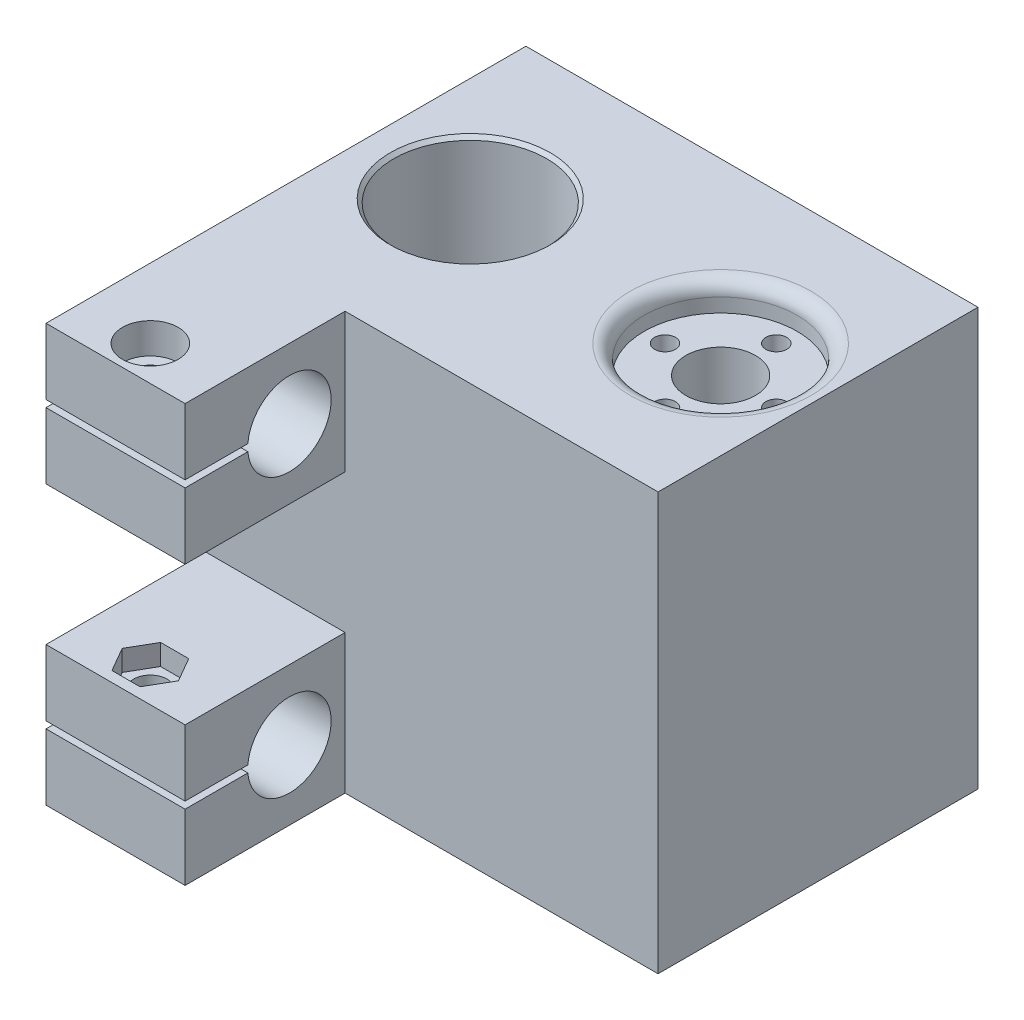
SolidWorks part; units mm, degrees
material "ABS"
ref_plane "Спереди" through (0, 0, 0) normal (0, 0, 1) x (1, 0, 0)
ref_plane "Сверху" through (0, 0, 0) normal (0, 1, 0) x (1, 0, 0)
ref_plane "Справа" through (0, 0, 0) normal (1, 0, 0) x (0, 0, -1)
sketch "Эскиз1" plane through (0, 0, 0) normal (0, 1, 0) x (1, 0, 0)
  line L0 (0, 0) -> (0, 46)
  line L1 (0, 46) -> (65, 46)
  line L2 (65, 46) -> (65, 0)
  line L3 (65, 0) -> (0, 0)
  line L4 (0, 23) -> (65, 23) construction
  line L5 (51, 46) -> (51, 0) construction
  line L6 (15, 46) -> (15, 0) construction
  line L7 (65, 3) -> (0, 3) construction
  circle A0 centre (51, 23) radius 5
  circle A1 centre (15, 23) radius 11
  dimension "D3" = 10
  dimension "D5" = 22
  dimension "D1" = 23
  dimension "D2" = 15
  dimension "D4" = 36
  dimension "D6" = 23
  dimension "D8" = 46
  dimension "D9" = 20
  dimension "D10" = 3
extrude "Бобышка-Вытянуть1" add sketch "Эскиз1" along normal blind 60
sketch "Эскиз3" plane through (0, 0, 0) normal (-1, 0, 0) x (0, 0, 1)
  line L0 (0, 60) -> (23, 60)
  line L1 (0, 60) -> (0, 0) construction
  line L2 (23, 0) -> (0, 0)
  line L3 (0, 40) -> (0, 60)
  line L4 (8, 50) -> (8, 10) construction
  line L5 (0, 20) -> (0, 0)
  line L6 (23, 60) -> (23, 50.5)
  line L7 (23, 40) -> (0, 40)
  line L8 (23, 50.5) -> (13.9791, 50.5)
  line L9 (0, 20) -> (23, 20)
  line L10 (23, 20) -> (23, 10.5)
  line L11 (23, 49.5) -> (13.9791, 49.5)
  line L12 (8, 50) -> (26.9195, 50) construction
  line L13 (23, 49.5) -> (23, 40)
  line L14 (23, 10.5) -> (13.9791, 10.5)
  line L15 (13.9791, 9.5) -> (23, 9.5)
  line L16 (23, 9.5) -> (23, 0)
  line L17 (8, 10) -> (27.7676, 10) construction
  arc A0 (13.9791, 50.5) -> (13.9791, 49.5) centre (8, 50) ccw
  arc A1 (13.9791, 10.5) -> (13.9791, 9.5) centre (8, 10) ccw
  dimension "D1" = 1
  dimension "D2" = 10
  dimension "D4" = 6
  dimension "D8" = 6
  dimension "D3" = 10
  dimension "D5" = 20
  dimension "D6" = 20
  dimension "D7" = 1
  dimension "D9" = 8
  dimension "D10" = 23
extrude "Бобышка-Вытянуть3" add sketch "Эскиз3" against normal blind 20
sketch "Эскиз18" plane through (0, 60, 0) normal (0, 1, 0) x (1, 0, 0)
  circle A0 centre (51, 23) radius 11
  dimension "D1" = 22
extrude "Вырез-Вытянуть8" cut sketch "Эскиз18" against normal blind 4
sketch "Эскиз20" plane through (0, 56, 0) normal (0, 1, 0) x (1, 0, 0)
  line L0 (51, 15) -> (51, 31) construction
  line L1 (43, 23) -> (59, 23) construction
  circle A0 centre (43, 23) radius 1.5
  circle A1 centre (59, 23) radius 1.5
  circle A2 centre (51, 31) radius 1.5
  circle A3 centre (51, 15) radius 1.5
  dimension "D1" = 3
  dimension "D2" = 16
  dimension "D3" = 16
extrude "Вырез-Вытянуть9" cut sketch "Эскиз20" against normal up to surface (56 mm away) up to face at (51, 0, -18)
fillet "Скругление4" radius 2 1 edges at (51, 60, -12)
sketch "Эскиз28" plane through (0, 0, 0) normal (0, -1, 0) x (-1, 0, 0)
  circle A0 centre (-51, 23) radius 11
  dimension "D1" = 22
extrude "Вырез-Вытянуть10" cut sketch "Эскиз28" against normal blind 4
chamfer "Фаска1" distance 0.5 1 edges at (15, 60, -12)
fillet "Скругление5" radius 2 1 edges at (51, 0, -34)
chamfer "Фаска2" distance 0.5 1 edges at (15, 0, -12)
hole_wizard "Цековка для  винта с внутренним шестигранником M41" positions "Эскиз21" profile "Эскиз23" counterbore size "M4" standard "DIN"
sketch "Эскиз21" plane through (0, 60, 0) normal (0, 1, 0) x (1, 0, 0)
  line L0 (10, -23) -> (10, -3.6448) construction
  line L1 (20, -23) -> (0, -23) construction
  line L3 (0, 46) -> (0, -23) construction
  point P0 (10, -18)
  dimension "D1" = 10
  dimension "D2" = 5
sketch "Эскиз23" plane through (10, 60, 18) normal (1, 0, 0) x (0, 0, 1)
  line L0 (0, 0) -> (0, 21.4411)
  line L1 (0, 21.4411) -> (2.4, 19.999)
  line L2 (2.4, 19.999) -> (2.4, 4.4)
  line L3 (2.4, 4.4) -> (4, 4.4)
  line L4 (4, 4.4) -> (4, 0)
  line L5 (4, 0) -> (0, 0)
  line L10 (0, 21.4411) -> (-2.4, 19.999) construction
  line L11 (0, -6.35) -> (0, 107.95) construction
  dimension "Диаметр отверстия" = 4.8
  dimension "Глубина отверстия" = 19.999
  dimension "Диаметр цековки" = 8
  dimension "Глубина цековки" = 4.4
  dimension "Угол заточки сверла" = 118
hole_wizard "Цековка для  винта с внутренним шестигранником M42" positions "Эскиз26" profile "Эскиз27" counterbore size "M4" standard "DIN"
sketch "Эскиз26" plane through (0, 0, 0) normal (0, -1, 0) x (-1, 0, 0)
  line L0 (0, 46) -> (0, -23) construction
  line L1 (-20, -23) -> (0, -23) construction
  point P0 (-10, -18)
  dimension "D1" = 10
  dimension "D2" = 5
sketch "Эскиз27" plane through (10, 0, 18) normal (1, 0, 0) x (0, 0, -1)
  line L0 (0, 0) -> (0, 21.4411)
  line L1 (0, 21.4411) -> (2.4, 19.999)
  line L2 (2.4, 19.999) -> (2.4, 4.4)
  line L3 (2.4, 4.4) -> (4, 4.4)
  line L4 (4, 4.4) -> (4, 0)
  line L5 (4, 0) -> (0, 0)
  line L10 (0, 21.4411) -> (-2.4, 19.999) construction
  line L11 (0, -6.35) -> (0, 107.95) construction
  dimension "Диаметр отверстия" = 4.8
  dimension "Глубина отверстия" = 19.999
  dimension "Диаметр цековки" = 8
  dimension "Глубина цековки" = 4.4
  dimension "Угол заточки сверла" = 118
sketch "Эскиз29" plane through (0, 20, 0) normal (0, 1, 0) x (1, 0, 0)
  line L0 (14.0415, -18) -> (5.9585, -18) construction
  line L1 (10, -21.5) -> (10, -14.5) construction
  line L2 (7.9793, -21.5) -> (12.0207, -21.5)
  line L3 (12.0207, -21.5) -> (14.0415, -18)
  line L4 (14.0415, -18) -> (12.0207, -14.5)
  line L5 (12.0207, -14.5) -> (7.9793, -14.5)
  line L6 (7.9793, -14.5) -> (5.9585, -18)
  line L7 (5.9585, -18) -> (7.9793, -21.5)
  line L8 (20, -23) -> (0, -23) construction
  circle A0 centre (10, -18) radius 2.4 construction
  point P22 (10, -18)
  dimension "D1" = 7
  dimension "D2" = 7
  dimension "D3" = 7
extrude "Вырез-Вытянуть11" cut sketch "Эскиз29" against normal blind 3
sketch "Эскиз34" plane through (0, 40, 0) normal (0, -1, 0) x (-1, 0, 0)
  line L0 (-14.0415, -18) -> (-5.9585, -18) construction
  line L1 (-10, -21.5) -> (-10, -14.5) construction
  line L2 (-7.9793, -21.5) -> (-12.0207, -21.5)
  line L3 (-12.0207, -21.5) -> (-14.0415, -18)
  line L4 (-14.0415, -18) -> (-12.0207, -14.5)
  line L5 (-12.0207, -14.5) -> (-7.9793, -14.5)
  line L6 (-7.9793, -14.5) -> (-5.9585, -18)
  line L7 (-5.9585, -18) -> (-7.9793, -21.5)
  dimension "D1" = 7
  dimension "D2" = 7
  dimension "D3" = 7
extrude "Вырез-Вытянуть12" cut sketch "Эскиз34" against normal blind 3
